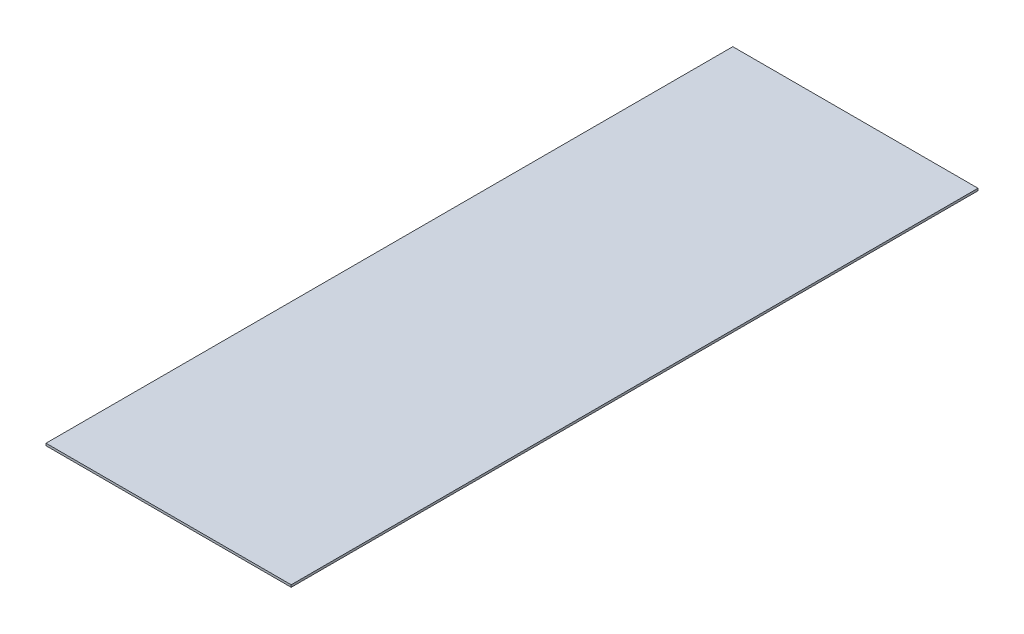
SolidWorks part; units mm, degrees
material "Acrylic (Medium-high impact)"
ref_plane "Front Plane" through (0, 0, 0) normal (0, 0, 1) x (1, 0, 0)
ref_plane "Top Plane" through (0, 0, 0) normal (0, 1, 0) x (1, 0, 0)
ref_plane "Right Plane" through (0, 0, 0) normal (1, 0, 0) x (0, 0, -1)
sketch "Sketch1" plane through (0, 0, 0) normal (0, 1, 0) x (1, 0, 0)
  line L1 (-220, -616.25) -> (220, -616.25)
  line L2 (-220, -616.25) -> (-220, 616.25)
  line L3 (-220, 616.25) -> (220, 616.25)
  line L4 (220, -616.25) -> (220, 616.25)
  line L5 (-220, -616.25) -> (220, 616.25) construction
  line L6 (-220, 616.25) -> (220, -616.25) construction
  point P0 (0, 0)
  dimension "D1" = 1232.5
  dimension "D2" = 440
extrude "Boss-Extrude1" add sketch "Sketch1" along normal mid plane 4
